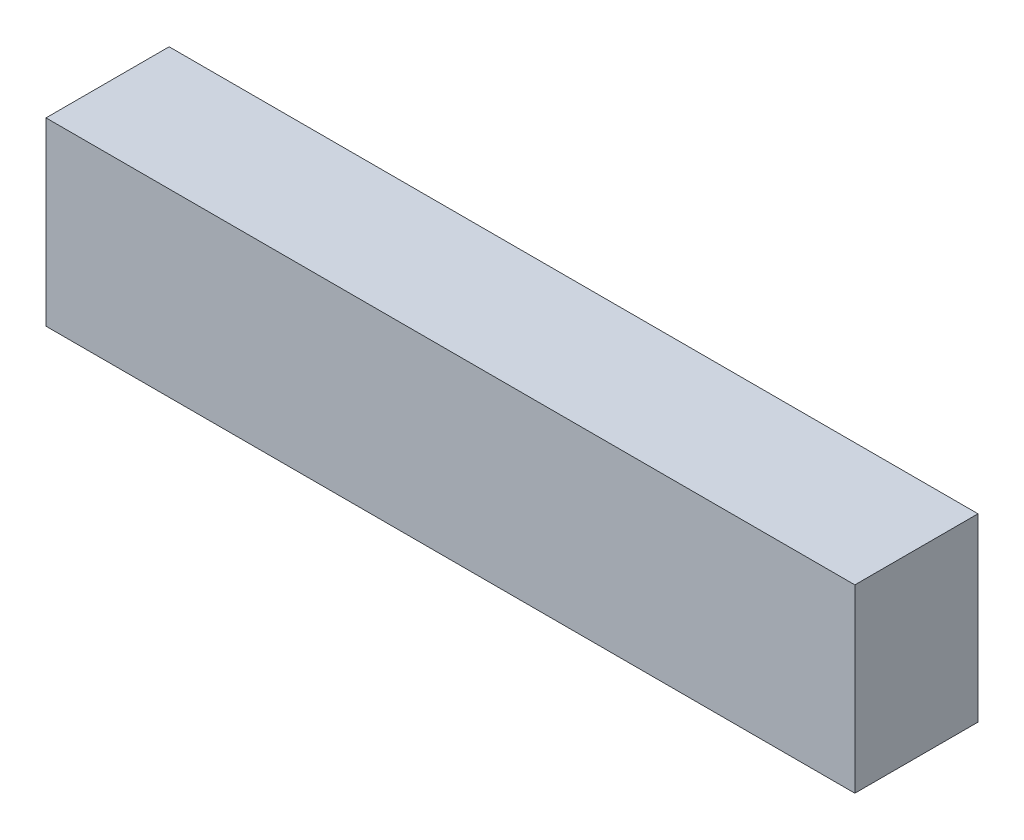
SolidWorks part; units mm, degrees
ref_plane "Front Plane" through (0, 0, 0) normal (0, 0, 1) x (1, 0, 0)
ref_plane "Top Plane" through (0, 0, 0) normal (0, 1, 0) x (1, 0, 0)
ref_plane "Right Plane" through (0, 0, 0) normal (1, 0, 0) x (0, 0, -1)
sketch "Sketch1" plane through (0, 0, 0) normal (0, 1, 0) x (1, 0, 0)
  line L1 (-19.05, -2.9) -> (19.05, -2.9)
  line L2 (-19.05, -2.9) -> (-19.05, 2.9)
  line L3 (-19.05, 2.9) -> (19.05, 2.9)
  line L4 (19.05, -2.9) -> (19.05, 2.9)
  line L5 (-19.05, -2.9) -> (19.05, 2.9) construction
  line L6 (-19.05, 2.9) -> (19.05, -2.9) construction
  point P0 (0, 0)
  dimension "D1" = 38.1
  dimension "D2" = 5.8
extrude "Boss-Extrude1" add sketch "Sketch1" along normal blind 8.5
